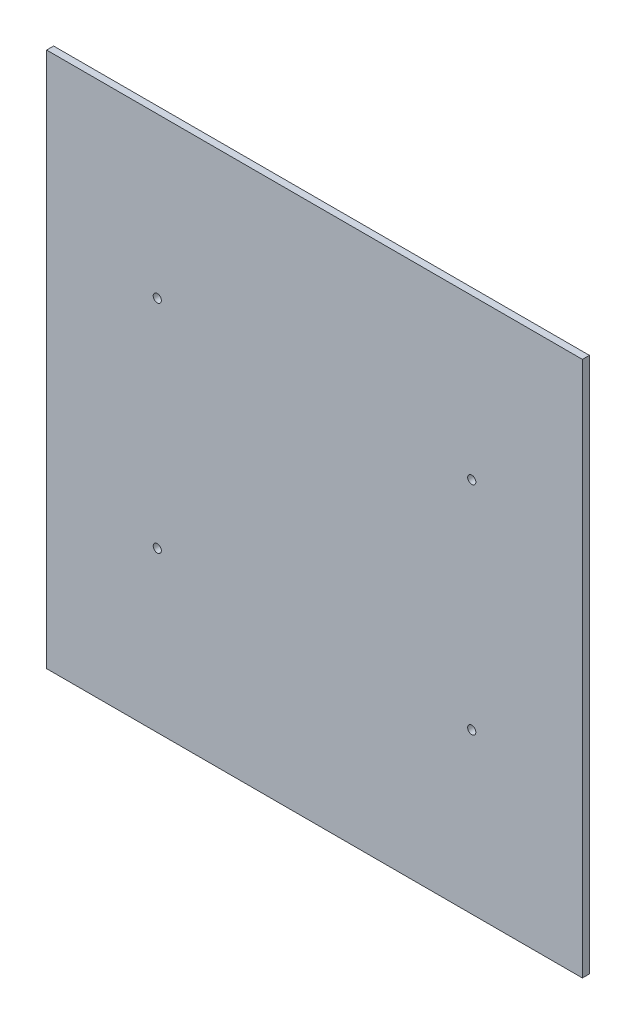
SolidWorks part; units mm, degrees
ref_plane "Front Plane" through (0, 0, 0) normal (0, 0, 1) x (1, 0, 0)
ref_plane "Top Plane" through (0, 0, 0) normal (0, 1, 0) x (1, 0, 0)
ref_plane "Right Plane" through (0, 0, 0) normal (1, 0, 0) x (0, 0, -1)
sketch "Sketch1" plane through (0, 0, 0) normal (0, 0, 1) x (1, 0, 0)
  line L1 (-198.3129, 43.3479) -> (31.6871, 43.3479)
  line L2 (-198.3129, 43.3479) -> (-198.3129, -186.6521)
  line L3 (-198.3129, -186.6521) -> (31.6871, -186.6521)
  line L4 (31.6871, 43.3479) -> (31.6871, -186.6521)
  dimension "D1" = 230
extrude "Boss-Extrude1" add sketch "Sketch1" along normal blind 3
sketch "Sketch2" plane through (0, 0, 3) normal (0, 0, 1) x (1, 0, 0)
  line L0 (31.6871, -186.6521) -> (31.6871, 43.3479) construction
  line L1 (-150.8129, -25.1521) -> (-15.8129, -25.1521) construction
  line L2 (-150.8129, -25.1521) -> (-150.8129, -118.1521) construction
  line L3 (-150.8129, -118.1521) -> (-15.8129, -118.1521) construction
  line L4 (-15.8129, -25.1521) -> (-15.8129, -118.1521) construction
  line L5 (31.6871, 43.3479) -> (-198.3129, 43.3479) construction
  circle A0 centre (-15.8129, -25.1521) radius 1.75
  circle A1 centre (-15.8129, -118.1521) radius 1.75
  circle A2 centre (-150.8129, -118.1521) radius 1.75
  circle A3 centre (-150.8129, -25.1521) radius 1.75
  point P10 (31.6871, -71.6521)
  point P13 (-83.3129, 43.3479)
  dimension "D1" = 3.5
  dimension "D2" = 93
  dimension "D3" = 46.5
  dimension "D4" = 135
  dimension "D5" = 67.5
extrude "Cut-Extrude1" cut sketch "Sketch2" against normal blind 10
